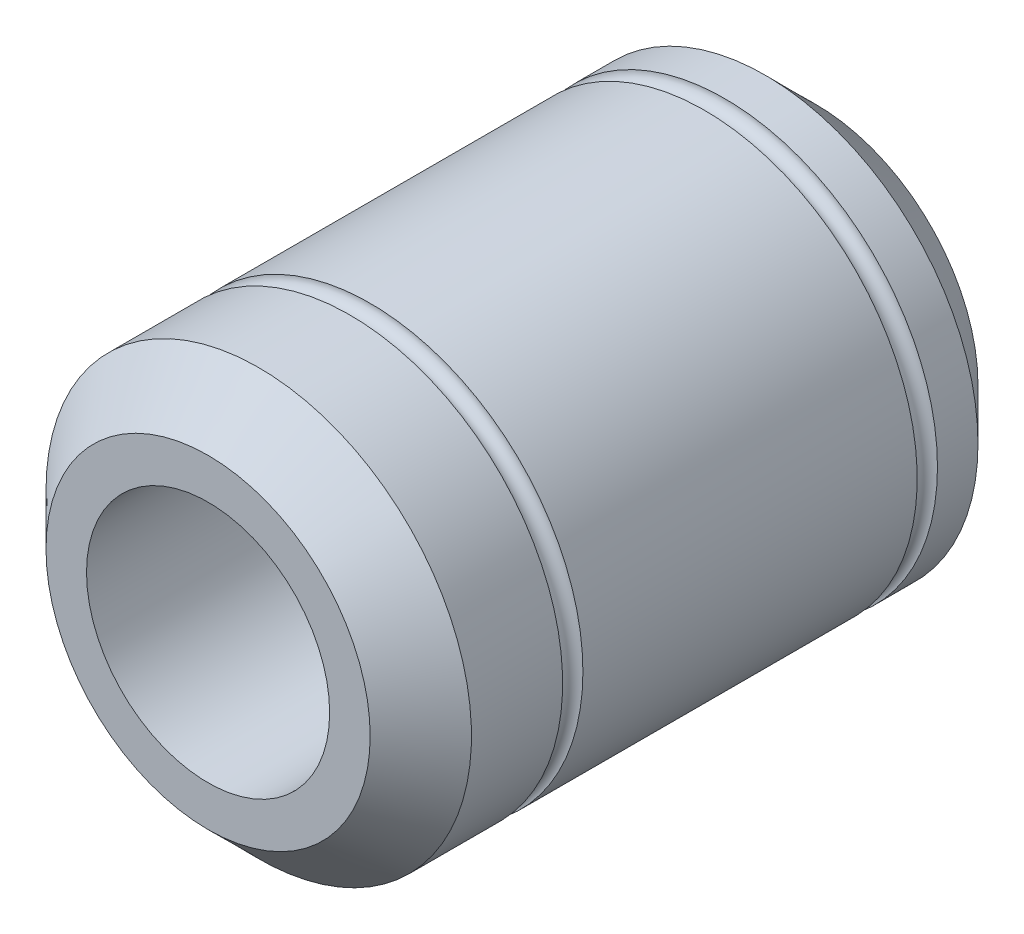
SolidWorks part; units mm, degrees
material "合金钢"
ref_plane "前视基准面" through (0, 0, 0) normal (0, 0, 1) x (1, 0, 0)
ref_plane "上视基准面" through (0, 0, 0) normal (0, 1, 0) x (1, 0, 0)
ref_plane "右视基准面" through (0, 0, 0) normal (1, 0, 0) x (0, 0, -1)
sketch "草图1" plane through (0, 0, 0) normal (0, 0, 1) x (1, 0, 0)
  circle A0 centre (0, 0) radius 6
  circle A1 centre (0, 0) radius 10.5
  dimension "D1" = 21
  dimension "D2" = 12
extrude "凸台-拉伸1" add sketch "草图1" against normal blind 30
sketch "草图2" plane through (0, 0, 0) normal (0, 1, 0) x (1, 0, 0)
  line L0 (0, 40.5514) -> (0, -3.4262) construction
  line L1 (7.5, 30.5) -> (11, 27)
  line L2 (11, 27) -> (11, 30.5)
  line L3 (11, 30.5) -> (7.5, 30.5)
  line L4 (11, 3) -> (7.5, -0.5)
  line L5 (7.5, -0.5) -> (11, -0.5)
  line L6 (11, -0.5) -> (11, 3)
  line L7 (10.5, 30) -> (-10.5, 30) construction
  point P9 (11, 28.75)
  dimension "D1" = 0.5
  dimension "D2" = 11
  dimension "D3" = 11
  dimension "D4" = 135
  dimension "D5" = 45
  dimension "D6" = 3.5
  dimension "D7" = 3.5
  dimension "D8" = 0.5
revolve "切除-旋转3" cut sketch "草图2" angle 360 about L0
sketch "草图4" plane through (0, 0, 0) normal (0, 1, 0) x (1, 0, 0)
  line L0 (10.5, 2.5) -> (10.5, 27.5) construction
  line L1 (0, 36.8324) -> (0, -3.9559) construction
  line L3 (-10.5, 2.5) -> (10.5, 2.5) construction
  line L4 (10.5, 30) -> (-10.5, 30) construction
  circle A0 centre (10.5, 25) radius 0.5
  circle A1 centre (10.5, 7.5) radius 0.5
  dimension "D1" = 1
  dimension "D2" = 1
  dimension "D3" = 5
  dimension "D4" = 5
revolve "切除-旋转4" cut sketch "草图4" angle 360 about L1
